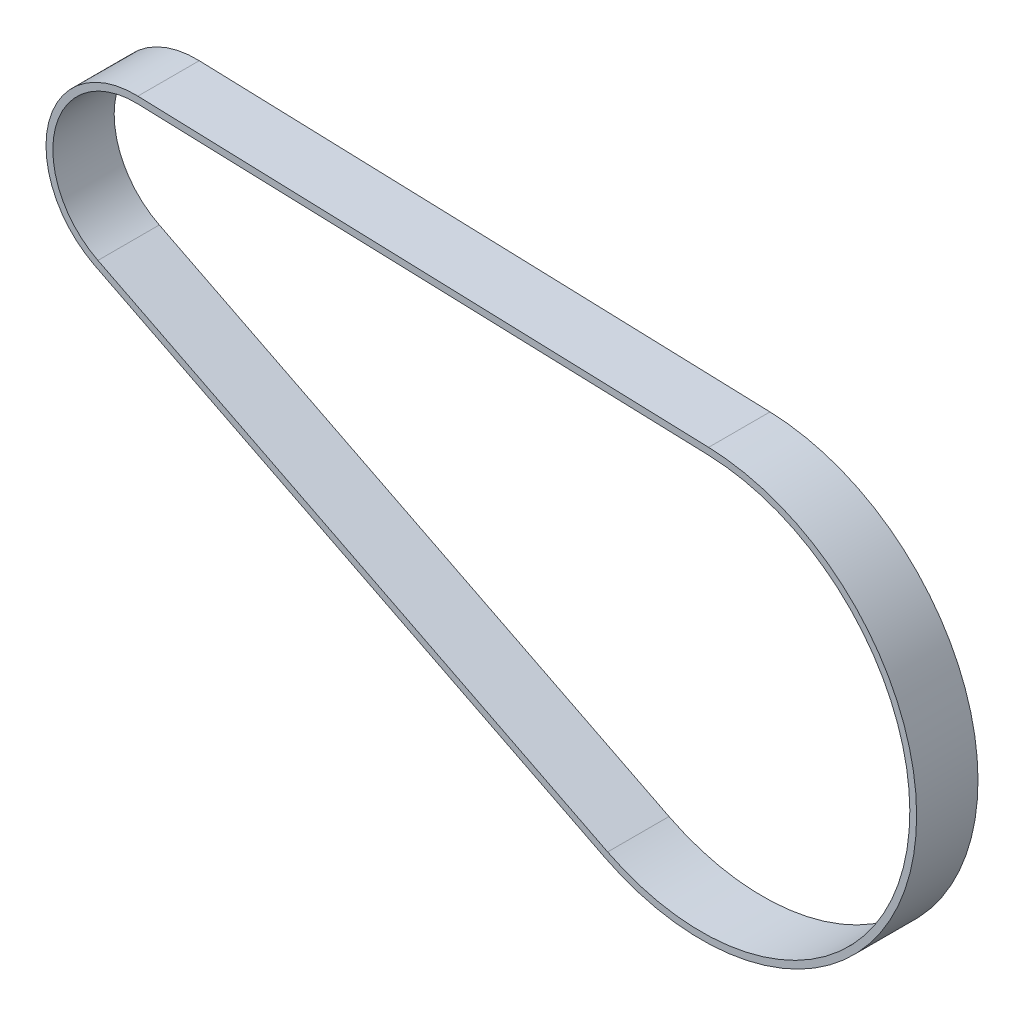
SolidWorks part; units mm, degrees
ref_plane "Front Plane" through (0, 0, 0) normal (0, 0, 1) x (1, 0, 0)
ref_plane "Top Plane" through (0, 0, 0) normal (0, 1, 0) x (1, 0, 0)
ref_plane "Right Plane" through (0, 0, 0) normal (1, 0, 0) x (0, 0, -1)
sketch "Sketch2" plane through (0, 0, 0) normal (0, 0, 1) x (1, 0, 0)
  line L0 (0, 0) -> (1, 0) construction
  line L1 (0, 0) -> (0, 1) construction
  line L2 (-13.7733, -27.269) -> (-88.5339, 10.492)
  line L3 (-82.7044, 33.2913) -> (1.0059, 30.5334)
  arc A0 (1.0059, 30.5334) -> (-13.7733, -27.269) centre (0, 0) cw
  arc A1 (-88.5339, 10.492) -> (-82.7044, 33.2913) centre (-83.1012, 21.2478) cw
extrude "Extrude-Thin1" add sketch "Sketch2" along normal blind 4.5 and the other way blind 4.5 thin thin type one direction wall 1
